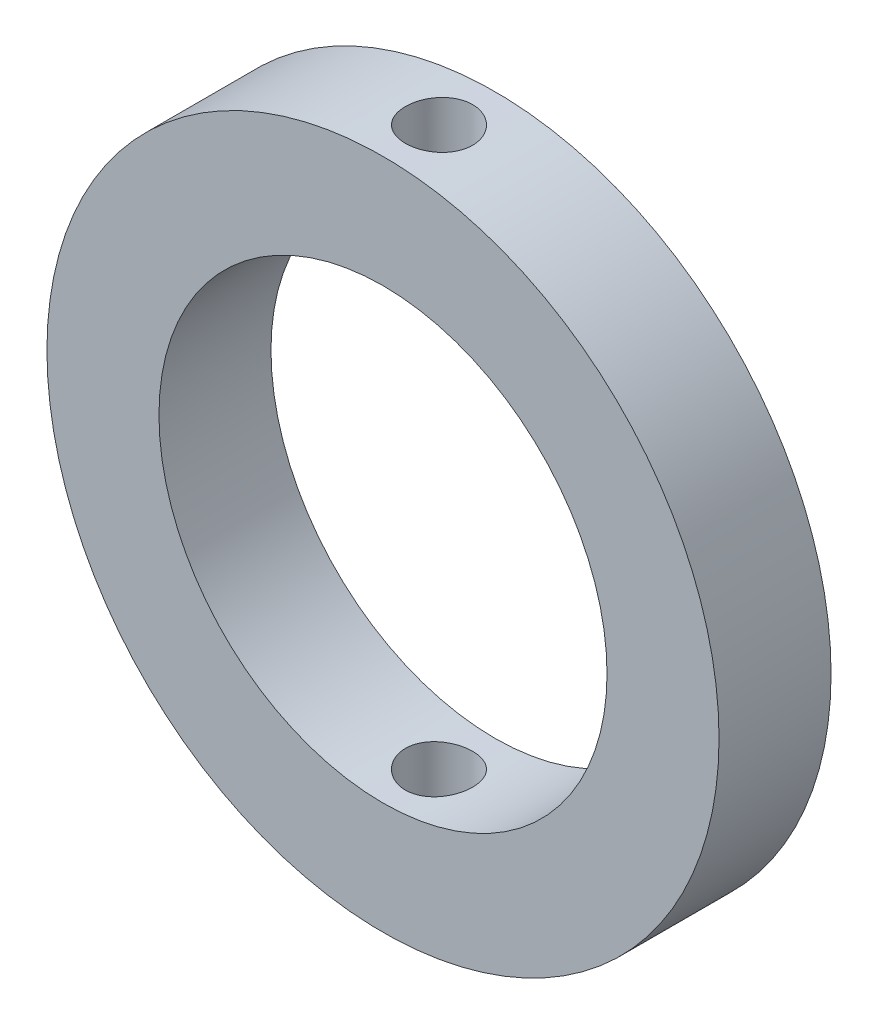
SolidWorks part; units mm, degrees
ref_plane "Front Plane" through (0, 0, 0) normal (0, 0, 1) x (1, 0, 0)
ref_plane "Top Plane" through (0, 0, 0) normal (0, 1, 0) x (1, 0, 0)
ref_plane "Right Plane" through (0, 0, 0) normal (1, 0, 0) x (0, 0, -1)
sketch "Sketch1" plane through (0, 0, 0) normal (0, 0, 1) x (1, 0, 0)
  circle A0 centre (0, 0) radius 20
  circle A1 centre (0, 0) radius 30
  dimension "D1" = 40
  dimension "D2" = 60
extrude "Boss-Extrude1" add sketch "Sketch1" along normal blind 10
sketch "Sketch2" plane through (0, 0, 0) normal (0, 1, 0) x (1, 0, 0)
  line L0 (-30, -5) -> (30, -5) construction
  line L1 (-30, 0) -> (-30, -10) construction
  line L2 (30, -10) -> (30, 0) construction
  circle A0 centre (0, -5) radius 3
extrude "Cut-Extrude1" cut sketch "Sketch2" against normal through all both and the other way through all
scale "Scale1" scale about centroid uniform scaling yes scale factor 0.35
